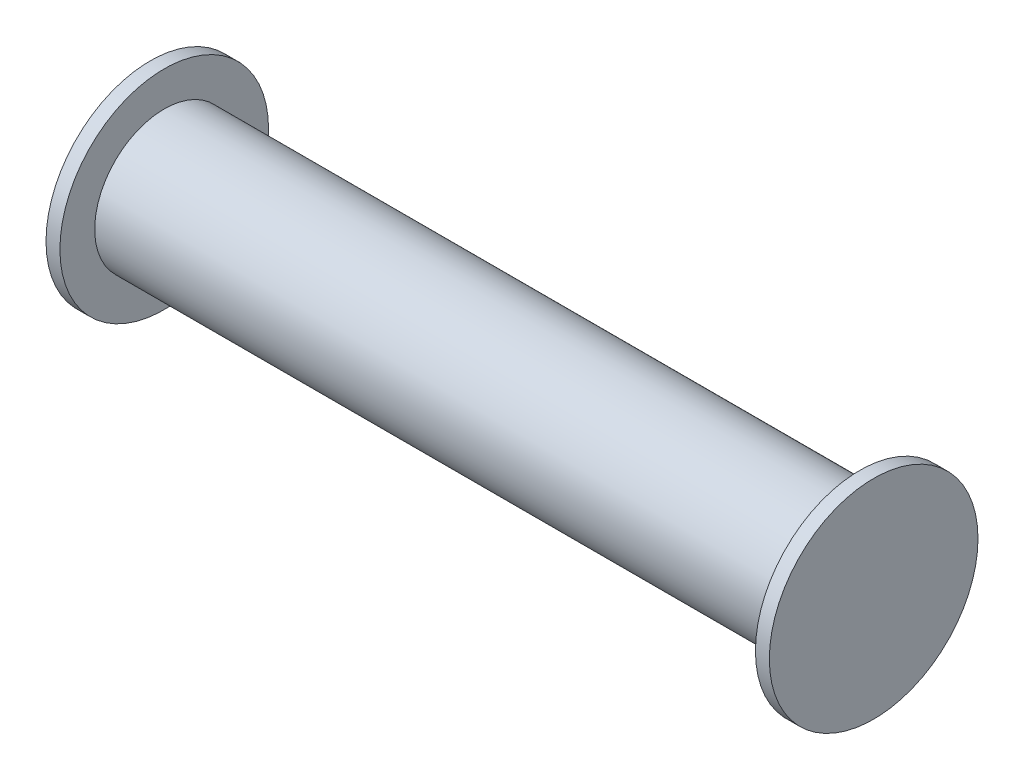
SolidWorks part; units mm, degrees
ref_plane "Front Plane"
ref_plane "Top Plane" through (0, 0, 0) normal (0, 1, 0) x (1, 0, 0)
ref_plane "Right Plane" through (0, 0, 0) normal (1, 0, 0) x (0, 0, -1)
sketch "Sketch1" plane through (0, 0, 0) normal (1, 0, 0) x (0, 0, -1)
  circle A0 centre (0, 0) radius 10
  circle A1 centre (0, 0) radius 8
  dimension "D1" = 20
  dimension "D2" = 16
extrude "Boss-Extrude1" add sketch "Sketch1" along normal mid plane 100
sketch "Sketch2" plane through (50, 0, 0) normal (1, 0, 0) x (0, 0, -1)
  circle A0 centre (0, 0) radius 15
  dimension "D1" = 30
extrude "Boss-Extrude2" add sketch "Sketch2" along normal blind 2 separate body
sketch "Sketch3" plane through (-50, 0, 0) normal (-1, 0, 0) x (0, 0, 1)
  circle A0 centre (0, 0) radius 15
  dimension "D1" = 30
extrude "Boss-Extrude3" add sketch "Sketch3" along normal blind 2 separate body
